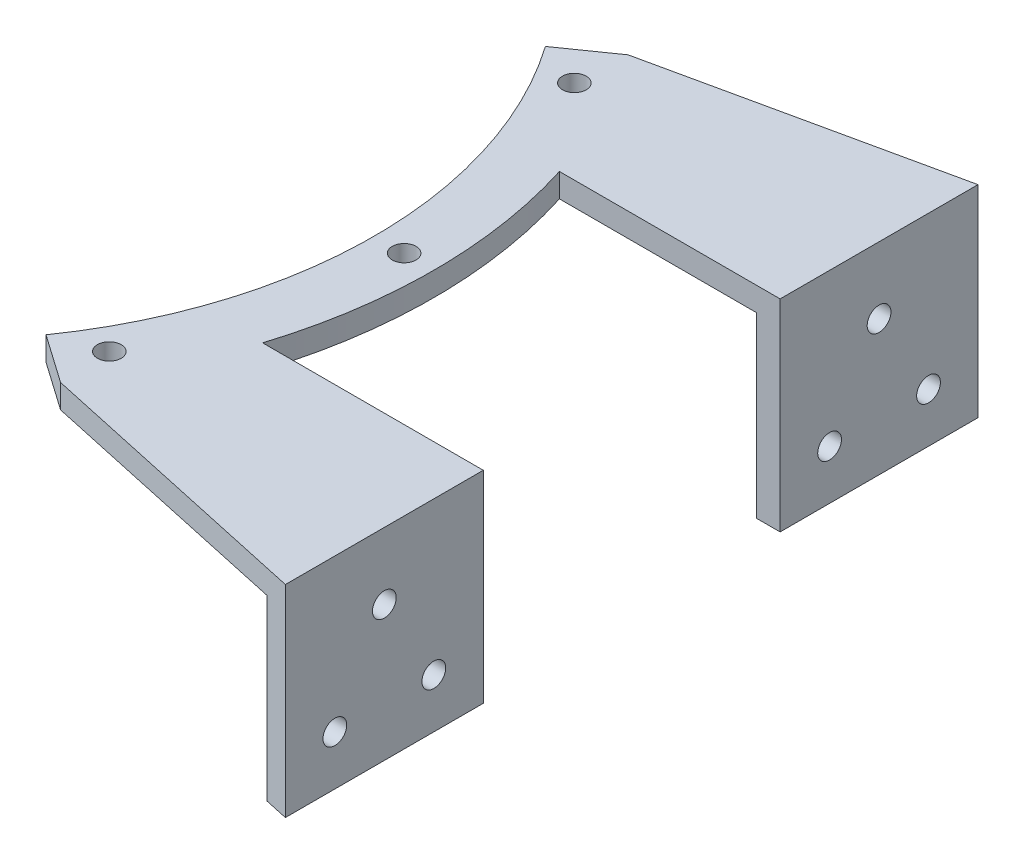
SolidWorks part; units mm, degrees
ref_plane "Front Plane" through (0, 0, 0) normal (0, 0, 1) x (1, 0, 0)
ref_plane "Top Plane" through (0, 0, 0) normal (0, 1, 0) x (1, 0, 0)
ref_plane "Right Plane" through (0, 0, 0) normal (1, 0, 0) x (0, 0, -1)
sketch "Sketch1" plane through (0, 0, 0) normal (0, 1, 0) x (1, 0, 0)
  line L0 (0, 0) -> (250, 0) construction
  line L1 (0, 0) -> (216.5064, 125) construction
  line L2 (0, 0) -> (216.5064, -125) construction
  line L3 (216.5064, 125) -> (216.5064, -125) construction
  line L5 (204.788, 143.3941) -> (204.788, -143.3941) construction
  line L11 (350, 175) -> (350, 75)
  line L12 (350, 75) -> (238.4848, 75)
  line L13 (350, -175) -> (350, -75)
  line L14 (350, -75) -> (238.4848, -75)
  line L15 (0, 0) -> (204.788, 143.3941) construction
  line L16 (0, 0) -> (204.788, -143.3941) construction
  line L17 (180.2134, 126.1868) -> (204.788, 143.3941)
  line L18 (180.2134, -126.1868) -> (204.788, -143.3941)
  line L21 (204.788, 143.3941) -> (350, 175)
  line L22 (204.788, -143.3941) -> (350, -175)
  arc A0 (180.2134, -126.1868) -> (180.2134, 126.1868) centre (0, 0) ccw
  arc A1 (204.788, -143.3941) -> (204.788, 143.3941) centre (0, 0) ccw construction
  circle A2 centre (0, 0) radius 235 construction
  circle A3 centre (203.516, -117.5) radius 6
  circle A4 centre (235, 0) radius 6
  circle A5 centre (203.516, 117.5) radius 6
  arc A8 (238.4848, -75) -> (238.4848, 75) centre (0, 0) ccw
  dimension "D11" = 250
  dimension "D2" = 220
  dimension "D4" = 470
  dimension "D5" = 12
  dimension "D3" = 60
  dimension "D6" = 100
  dimension "D7" = 100
  dimension "D8" = 350
  dimension "D9" = 70
  dimension "D10" = 350
extrude "Boss-Extrude2" add sketch "Sketch1" along normal blind 12
sketch "Sketch2" plane through (0, 0, 0) normal (0, -1, 0) x (-1, 0, 0)
  line L0 (-350, -175) -> (-350, -75)
  line L1 (-350, -75) -> (-338, -75)
  line L2 (-350, -75) -> (-238.4848, -75) construction
  line L3 (-338, -75) -> (-338, -172.3882)
  line L4 (-204.788, -143.3941) -> (-350, -175) construction
  line L5 (-338, -172.3882) -> (-350, -175)
  line L6 (-350, 75) -> (-350, 175)
  line L7 (-350, 175) -> (-338, 172.3882)
  line L8 (-350, 175) -> (-204.788, 143.3941) construction
  line L9 (-338, 172.3882) -> (-338, 75)
  line L10 (-238.4848, 75) -> (-350, 75) construction
  line L11 (-338, 75) -> (-350, 75)
  dimension "D1" = 12
extrude "Boss-Extrude3" add sketch "Sketch2" along normal blind 90
sketch "Sketch4" plane through (338, 0, 0) normal (-1, 0, 0) x (0, 0, 1)
  line L0 (-60, -65) -> (-158.8275, -65) construction
  line L3 (0, 0) -> (0, -141.9458) construction
  circle A0 centre (-150, -65) radius 6
  circle A1 centre (-100, -65) radius 6
  circle A2 centre (-125, -21.6987) radius 6
  circle A3 centre (150, -65) radius 6
  circle A4 centre (125, -21.6987) radius 6
  circle A5 centre (100, -65) radius 6
  dimension "D5" = 12
  dimension "D1" = 65
  dimension "D2" = 50
  dimension "D3" = 50
  dimension "D4" = 50
  dimension "D6" = 150
extrude "Cut-Extrude1" cut sketch "Sketch4" against normal through all
equation "\"mbtOD\" = 600"
equation "\"mbtT\" = 6"
equation "\"mbtL\" = 3000"
equation "\"mbtFlangeOD\" = 700"
equation "\"mbtFlangeT\" = 12"
equation "\"mbtFlangeBoltCircleDia\" = 650"
equation "\"mbtFlangeHoleDia\" = 12"
equation "\"mbtOringSize\" = 10 "
equation "\"mbtOringDia\" = 620"
equation "\"mbtWidth\" = 2250"
equation "\"skiWidth\" = 1250"
equation "\"mbtCapL\" = 500"
equation "\"vbtRearOD\" = 500"
equation "\"vbtRearT\" = 6.25"
equation "\"vbtRearFlangeOD\" = 600"
equation "\"vbtRearFlangeT\" = 12"
equation "\"vbtRearBoltHoleDia\" = 12"
equation "\"vbtFrontOD\" = 440"
equation "\"vbtFrontT\" = 25"
equation "\"vbtFrontFlangeOD\" = 500"
equation "\"vbtFrontFlangeT\" = 12"
equation "\"vbtFrontBoltHoleDia\" = 12"
equation "\"D8@Sketch1\"=\"vbtFrontFlangeOD\"/2+100mm"
equation "\"D1@Boss-Extrude2\"=\"vbtRearFlangeT\""
equation "\"D11@Sketch1\"=\"vbtFrontFlangeOD\"/2"
equation "\"D2@Sketch1\"=\"vbtFrontOD\"/2"
equation "\"D4@Sketch1\"=(\"vbtFrontOD\"+\"vbtFrontFlangeOD\")/2"
equation "\"D5@Sketch1\"=\"vbtFrontBoltHoleDia\""
equation "\"D1@Sketch2\"=\"vbtFrontFlangeT\""
